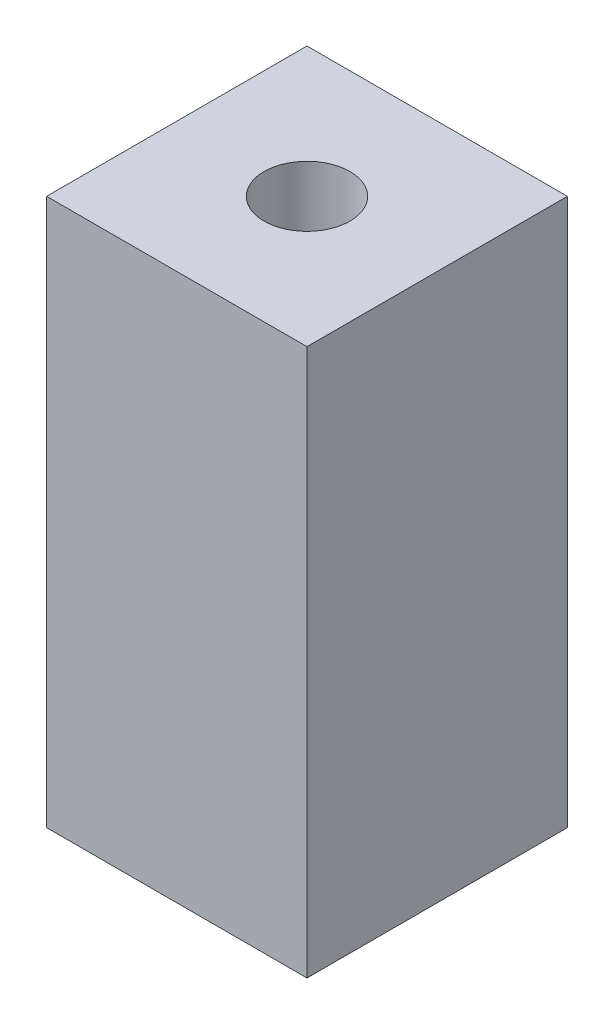
SolidWorks part; units mm, degrees
ref_plane "前视基准面" through (0, 0, 0) normal (0, 0, 1) x (1, 0, 0)
ref_plane "上视基准面" through (0, 0, 0) normal (0, 1, 0) x (1, 0, 0)
ref_plane "右视基准面" through (0, 0, 0) normal (1, 0, 0) x (0, 0, -1)
other "Configuration Table"
sketch "草图1" plane through (0, 0, 0) normal (0, 1, 0) x (1, 0, 0)
  line L1 (-2.5, 2.5) -> (2.5, 2.5)
  line L2 (-2.5, 2.5) -> (-2.5, -2.5)
  line L3 (-2.5, -2.5) -> (2.5, -2.5)
  line L4 (2.5, 2.5) -> (2.5, -2.5)
  line L5 (-2.5, 2.5) -> (2.5, -2.5) construction
  line L6 (-2.5, -2.5) -> (2.5, 2.5) construction
  circle A0 centre (0, 0) radius 0.825
  point P0 (0, 0)
  dimension "D3" = 1.65
  dimension "D1" = 5
  dimension "D2" = 5
extrude "凸台-拉伸1" add sketch "草图1" along normal blind 10.5
